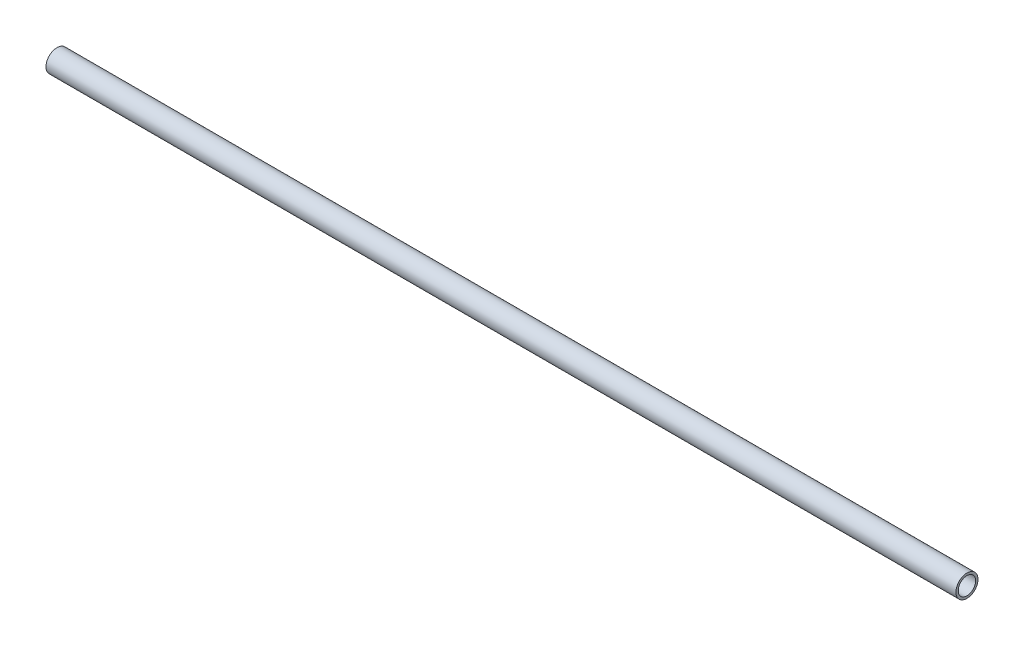
SolidWorks part; units mm, degrees
ref_plane "Alzado" through (0, 0, 0) normal (0, 0, 1) x (1, 0, 0)
ref_plane "Planta" through (0, 0, 0) normal (0, 1, 0) x (1, 0, 0)
ref_plane "Vista lateral" through (0, 0, 0) normal (1, 0, 0) x (0, 0, -1)
sketch "Croquis1" plane through (0, 0, 0) normal (1, 0, 0) x (0, 0, -1)
  circle A0 centre (0, 0) radius 19
  circle A1 centre (0, 0) radius 15
extrude "Saliente-Extruir1" add sketch "Croquis1" along normal blind 1565.549
